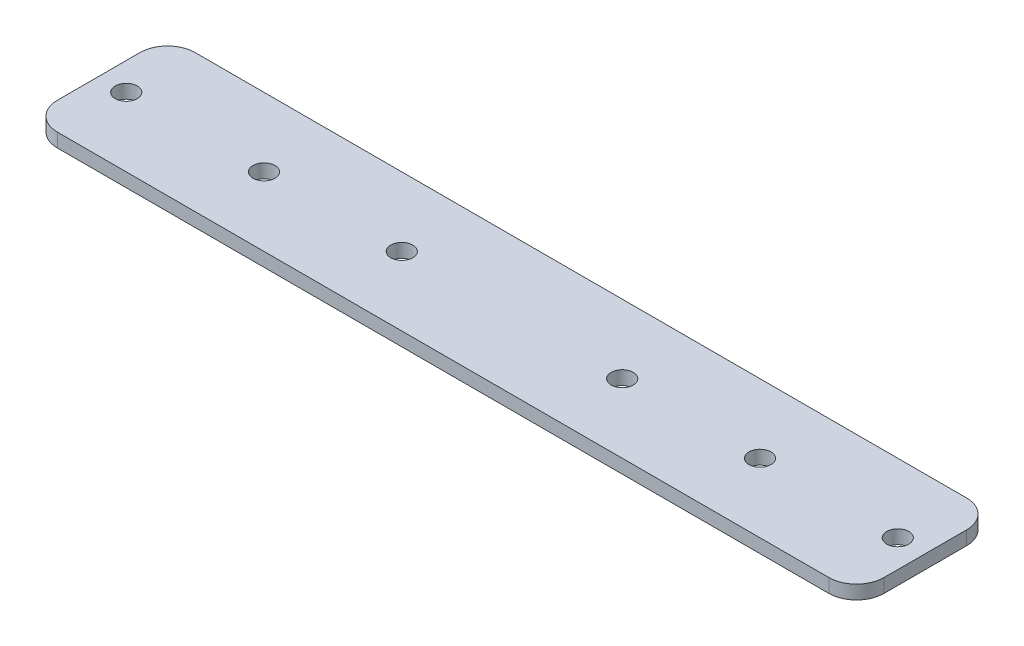
SolidWorks part; units mm, degrees
ref_plane "前视基准面" through (0, 0, 0) normal (0, 0, 1) x (1, 0, 0)
ref_plane "上视基准面" through (0, 0, 0) normal (0, 1, 0) x (1, 0, 0)
ref_plane "右视基准面" through (0, 0, 0) normal (1, 0, 0) x (0, 0, -1)
sketch "草图1" plane through (0, 0, 0) normal (0, 1, 0) x (1, 0, 0)
  line L1 (-60, -10) -> (60, -10)
  line L2 (-60, -10) -> (-60, 10)
  line L3 (-60, 10) -> (60, 10)
  line L4 (60, -10) -> (60, 10)
  line L5 (-60, -10) -> (60, 10) construction
  line L6 (-60, 10) -> (60, -10) construction
  circle A0 centre (16, 0) radius 1.6
  circle A1 centre (-16, 0) radius 1.6
  circle A2 centre (36, 0) radius 1.6
  circle A3 centre (56, 0) radius 1.6
  circle A5 centre (-36, 0) radius 1.6
  circle A6 centre (-56, 0) radius 1.6
  point P0 (0, 0)
  dimension "D1" = 16
  dimension "D2" = 16
  dimension "D3" = 20
  dimension "D4" = 20
  dimension "D5" = 20
  dimension "D6" = 20
extrude "凸台-拉伸1" add sketch "草图1" along normal blind 2
fillet "圆角1" radius 4 4 edges at (-60, 1, -10) (-60, 1, 10) (60, 1, 10) (60, 1, -10)
